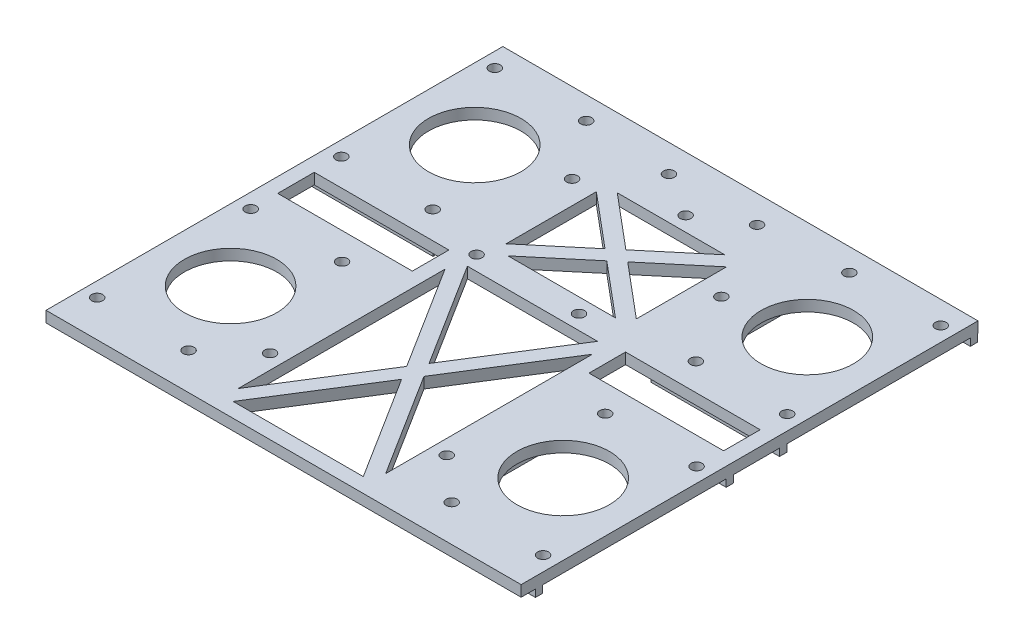
SolidWorks part; units mm, degrees
ref_plane "Front Plane" through (0, 0, 0) normal (0, 0, 1) x (1, 0, 0)
ref_plane "Top Plane" through (0, 0, 0) normal (0, 1, 0) x (1, 0, 0)
ref_plane "Right Plane" through (0, 0, 0) normal (1, 0, 0) x (0, 0, -1)
sketch "Sketch1" plane through (0, 0, 0) normal (0, 1, 0) x (1, 0, 0)
  line L1 (-65, 62.5) -> (65, 62.5)
  line L2 (-65, 62.5) -> (-65, -62.5)
  line L3 (-65, -62.5) -> (65, -62.5)
  line L4 (65, 62.5) -> (65, -62.5)
  line L5 (-65, 62.5) -> (65, -62.5) construction
  line L6 (-65, -62.5) -> (65, 62.5) construction
  point P0 (0, 0)
  dimension "D1" = 130
  dimension "D2" = 125
extrude "Boss-Extrude1" add sketch "Sketch1" along normal blind 5
sketch "Sketch2" plane through (0, 5, 0) normal (0, 1, 0) x (1, 0, 0)
  line L1 (-65, -62.5) -> (65, -62.5) construction
  line L2 (-65, 62.5) -> (-65, -62.5) construction
  circle A0 centre (-61, -52.5) radius 1.5
  circle A1 centre (-36, -52.5) radius 1.5
  circle A2 centre (-36, -10.5) radius 1.5
  circle A3 centre (-61, -10.5) radius 1.5
  circle A4 centre (-45.5, -31.5) radius 12.65
  dimension "D2" = 25.3
  dimension "D7" = 3
  dimension "D8" = 3
  dimension "D9" = 3
  dimension "D10" = 3
  dimension "D1" = 19.5
  dimension "D3" = 31
  dimension "D4" = 4
  dimension "D5" = 10
  dimension "D6" = 10
  dimension "D11" = 4
  dimension "D12" = 42
  dimension "D13" = 42
  dimension "D14" = 25
  dimension "D15" = 25
extrude "Cut-Extrude1" cut sketch "Sketch2" against normal blind 10
ref_plane "Plane1" through (0, 0, 0) normal (-1, 0, 0) x (0, 0, 1)
ref_plane "Plane2" through (0, 0, 0) normal (0, 0, 1) x (1, 0, 0)
mirror "Mirror3" about plane through (0, 0, 0) normal (-1, 0, 0) of "Cut-Extrude1"
sketch "Sketch4" plane through (0, 5, 0) normal (0, 1, 0) x (1, 0, 0)
  line L0 (0, 62.5) -> (0, 47.5) construction
  line L1 (65, 62.5) -> (-65, 62.5) construction
  line L2 (-12.0498, 55) -> (12.0498, 55) construction
  circle A0 centre (0, 47.5) radius 1.5
  circle A1 centre (12.0498, 55) radius 1.5
  circle A2 centre (-12.0498, 55) radius 1.5
  point P9 (0, 55)
  dimension "D2" = 3
  dimension "D3" = 3
  dimension "D4" = 3
  dimension "D1" = 15
  dimension "D5" = 24.0996
extrude "Cut-Extrude3" cut sketch "Sketch4" against normal blind 10
sketch "Sketch5" plane through (0, 0, 0) normal (0, -1, 0) x (1, 0, 0)
  line L0 (-58.15, 31.5) -> (-65, 31.5) construction
  line L1 (-65, -62.5) -> (-65, 62.5) construction
  line L2 (-65, 56.6) -> (-65, 6.4)
  line L3 (-65, 56.6) -> (-31.8, 56.6)
  line L4 (-31.8, 56.6) -> (-31.8, 6.4)
  line L5 (-31.8, 6.4) -> (-65, 6.4)
  line L6 (-65, 58.6) -> (-29.8, 58.6)
  line L7 (-29.8, 58.6) -> (-29.8, 4.4)
  line L8 (-29.8, 4.4) -> (-65, 4.4)
  line L9 (-65, 4.4) -> (-65, 6.4)
  line L10 (-65, 58.6) -> (-65, 56.6)
  circle A0 centre (-45.5, 31.5) radius 12.65 construction
  point P10 (-65, 31.5)
  line M39 (-65, 62.5) -> (-65, -62.5)
  dimension "D1" = 50.2
  dimension "D2" = 33.2
  dimension "D3" = 2
  dimension "D4" = 2
  dimension "D5" = 2
extrude "Boss-Extrude2" add sketch "Sketch5" along normal blind 2 contours L8 L7 L6 L3 L4 L5 M39
mirror "Mirror5" about plane through (0, 0, 0) normal (-1, 0, 0) of "Boss-Extrude2"
ref_plane "Plane3" through (0, 0, 0) normal (0, 0, 1) x (1, 0, 0)
ref_plane "Plane4" through (0, 0, -1.9) normal (0, 0, 1) x (1, 0, 0)
mirror "Mirror7" about plane through (0, 0, -1.9) normal (0, 0, 1) of "Mirror5", "Boss-Extrude2", "Mirror3", "Cut-Extrude1"
ref_plane "Plane5" through (0, 0, 0) normal (0, -1, 0) x (-1, 0, 0)
sketch "Sketch10" plane through (0, 0, 0) normal (0, -1, 0) x (-1, 0, 0)
  circle A0 centre (-24.17, -42.03) radius 1.5
  circle A1 centre (24.17, -42.03) radius 1.5
  circle A2 centre (-8.73, 9.6) radius 1.5
  circle A3 centre (19.29, 9.6) radius 1.5
  circle A4 centre (-24.17, 33.11) radius 1.5
  circle A5 centre (24.17, 40.6) radius 1.5
  dimension "D1" = 3
  dimension "D6" = 3
  dimension "D7" = 3
  dimension "D10" = 3
  dimension "D11" = 3
  dimension "D12" = 3
extrude "Cut-Extrude8" cut sketch "Sketch10" against normal through all
sketch "Sketch11" plane through (0, 0, 0) normal (0, -1, 0) x (1, 0, 0)
  circle A0 centre (-12.0498, -55) radius 2.65
  circle A1 centre (0, -47.5) radius 2.65
  circle A2 centre (12.0498, -55) radius 2.65
  circle A3 centre (-24.17, -40.6) radius 2.65
  circle A4 centre (24.17, -33.11) radius 2.65
  circle A5 centre (8.73, -9.6) radius 2.65
  circle A6 centre (-19.29, -9.6) radius 2.65
  circle A7 centre (-24.17, 42.03) radius 2.65
  circle A8 centre (24.17, 42.03) radius 2.65
  circle A9 centre (-61, -14.3) radius 2.65
  circle A10 centre (-36, -14.3) radius 2.65
  circle A11 centre (-61, -56.3) radius 2.65
  circle A12 centre (-36, -56.3) radius 2.65
  circle A13 centre (36, -56.3) radius 2.65
  circle A14 centre (61, -56.3) radius 2.65
  circle A15 centre (36, -14.3) radius 2.65
  circle A16 centre (61, -14.3) radius 2.65
  circle A17 centre (36, 10.5) radius 2.65
  circle A18 centre (61, 10.5) radius 2.65
  circle A19 centre (61, 52.5) radius 2.65
  circle A20 centre (36, 52.5) radius 2.65
  circle A21 centre (-36, 52.5) radius 2.65
  circle A22 centre (-36, 10.5) radius 2.65
  circle A23 centre (-61, 10.5) radius 2.65
  circle A24 centre (-61, 52.5) radius 2.65
  dimension "D1" = 5.3
  dimension "D2" = 5.3
  dimension "D3" = 5.3
  dimension "D4" = 5.3
  dimension "D5" = 5.3
  dimension "D6" = 5.3
  dimension "D7" = 5.3
  dimension "D8" = 5.3
  dimension "D9" = 5.3
  dimension "D10" = 5.3
  dimension "D11" = 5.3
  dimension "D12" = 5.3
  dimension "D13" = 5.3
  dimension "D14" = 5.3
  dimension "D15" = 5.3
  dimension "D16" = 5.3
  dimension "D17" = 5.3
  dimension "D18" = 5.3
  dimension "D19" = 5.3
  dimension "D20" = 5.3
  dimension "D21" = 5.3
  dimension "D22" = 5.3
  dimension "D23" = 5.3
  dimension "D24" = 5.3
  dimension "D25" = 5.3
extrude "Cut-Extrude9" cut sketch "Sketch11" against normal blind 0.5
sketch "Sketch12" plane through (0, 5, 0) normal (0, 1, 0) x (1, 0, 0)
  line L0 (-65, -62.5) -> (65, -62.5) construction
  line L1 (-20.17, 5.6) -> (20.17, 5.6)
  line L2 (-20.17, 5.6) -> (-20.17, -58.5)
  line L3 (-20.17, -58.5) -> (20.17, -58.5)
  line L4 (20.17, 5.6) -> (20.17, -58.5)
  line L5 (-20.17, 5.6) -> (20.17, -58.5) construction
  line L6 (-20.17, -58.5) -> (20.17, 5.6) construction
  line L7 (-17.8069, 5.6) -> (0, -22.6951)
  line L8 (20.17, -54.7451) -> (2.3631, -26.45)
  line L9 (2.3631, -26.45) -> (20.17, 1.8451)
  line L10 (0, -22.6951) -> (17.8069, 5.6)
  line L11 (-20.17, 1.8451) -> (-2.3631, -26.45)
  line L12 (-2.3631, -26.45) -> (-20.17, -54.7451)
  line L13 (-17.8069, -58.5) -> (0, -30.2049)
  line L14 (0, -30.2049) -> (17.8069, -58.5)
  circle A0 centre (-19.29, 9.6) radius 1.5 construction
  circle A1 centre (-24.17, -42.03) radius 1.5 construction
  circle A2 centre (24.17, -42.03) radius 1.5 construction
  dimension "D2" = 4
  dimension "D3" = 4
  dimension "D1" = 4
  dimension "D4" = 4
  dimension "D5" = 2
  dimension "D6" = 2
  dimension "D7" = 2
  dimension "D8" = 2
extrude "Cut-Extrude10" cut sketch "Sketch12" against normal through all contours L12 L11 L2 | L7 L10 L1 | L9 L8 L4 | L14 L13 L3
sketch "Sketch13" plane through (0, 5, 0) normal (0, 1, 0) x (1, 0, 0)
  line L0 (-61, 14.3) -> (-61, -10.5) construction
  line L1 (-61, 1.9) -> (-61, -3.1)
  line L2 (-61, -3.1) -> (-24.17, -3.1)
  line L3 (-24.17, -3.1) -> (-24.17, 6.9)
  line L4 (-24.17, 6.9) -> (-61, 6.9)
  line L5 (-61, 6.9) -> (-61, 1.9)
  line L6 (-20.17, 1.8451) -> (-20.17, -54.7451) construction
  dimension "D1" = 10
  dimension "D2" = 5
  dimension "D3" = 4
extrude "Cut-Extrude11" cut sketch "Sketch13" against normal through all
mirror "Mirror9" about plane through (0, 0, 0) normal (-1, 0, 0) of "Cut-Extrude11"
sketch "Sketch14" plane through (0, 5, 0) normal (0, 1, 0) x (1, 0, 0)
  line L0 (-17.8069, 43.5) -> (17.8069, 13.6) construction
  line L1 (-17.8069, 43.5) -> (17.8069, 43.5)
  line L2 (-17.8069, 43.5) -> (-17.8069, 13.6)
  line L3 (-17.8069, 13.6) -> (17.8069, 13.6)
  line L4 (17.8069, 43.5) -> (17.8069, 13.6)
  line L5 (-17.8069, 13.6) -> (17.8069, 43.5) construction
  line L6 (-17.8069, 40.8886) -> (-3.1104, 28.55)
  line L7 (-3.1104, 28.55) -> (-17.8069, 16.2114)
  line L8 (-14.6965, 13.6) -> (0, 25.9386)
  line L9 (0, 25.9386) -> (14.6965, 13.6)
  line L10 (17.8069, 16.2114) -> (3.1104, 28.55)
  line L11 (3.1104, 28.55) -> (17.8069, 40.8886)
  line L12 (14.6965, 43.5) -> (0, 31.1614)
  line L13 (0, 31.1614) -> (-14.6965, 43.5)
  circle A0 centre (0, 47.5) radius 1.5 construction
  circle A1 centre (8.73, 9.6) radius 1.5 construction
  dimension "D1" = 4
  dimension "D2" = 4
  dimension "D3" = 2
  dimension "D4" = 2
  dimension "D5" = 2
  dimension "D6" = 2
  dimension "D7" = 2
  dimension "D8" = 2
  dimension "D9" = 2
  dimension "D10" = 2
extrude "Cut-Extrude12" cut sketch "Sketch14" against normal through all contours L7 L6 L2 | L13 L12 L1 | L11 L10 L4 | L9 L8 L3
sketch "Sketch15" plane through (0, 5, 0) normal (0, 1, 0) x (1, 0, 0)
  line L1 (-63.5, 58.8) -> (-58.5, 58.8)
  line L2 (-63.5, 58.8) -> (-63.5, 53.8)
  line L3 (-63.5, 53.8) -> (-58.5, 53.8)
  line L4 (65, -62.5) -> (65, 62.5)
  line L5 (65, 62.5) -> (-65, 62.5)
  line L6 (-65, 62.5) -> (-65, -62.5)
  line L7 (-65, -62.5) -> (65, -62.5)
  line L8 (65, -62.5) -> (65, 62.5)
  line L9 (65, 62.5) -> (-65, 62.5)
  line L10 (-65, 62.5) -> (-65, -62.5)
  line L11 (-65, -62.5) -> (65, -62.5)
  line L12 (-58.5, 58.8) -> (-58.5, 53.8)
  line L13 (-63.5, 58.8) -> (-58.5, 53.8) construction
  line L14 (-63.5, 53.8) -> (-58.5, 58.8) construction
  line L15 (-38.5, 58.8) -> (-33.5, 58.8)
  line L16 (-38.5, 58.8) -> (-38.5, 53.8)
  line L17 (-38.5, 53.8) -> (-33.5, 53.8)
  line L18 (-33.5, 58.8) -> (-33.5, 53.8)
  line L19 (-38.5, 58.8) -> (-33.5, 53.8) construction
  line L20 (-38.5, 53.8) -> (-33.5, 58.8) construction
  line L21 (-14.5498, 57.5) -> (-9.5498, 57.5)
  line L22 (-14.5498, 57.5) -> (-14.5498, 52.5)
  line L23 (-14.5498, 52.5) -> (-9.5498, 52.5)
  line L24 (-9.5498, 57.5) -> (-9.5498, 52.5)
  line L25 (-14.5498, 57.5) -> (-9.5498, 52.5) construction
  line L26 (-14.5498, 52.5) -> (-9.5498, 57.5) construction
  line L27 (-2.5, 50) -> (2.5, 50)
  line L28 (-2.5, 50) -> (-2.5, 45)
  line L29 (-2.5, 45) -> (2.5, 45)
  line L30 (2.5, 50) -> (2.5, 45)
  line L31 (-2.5, 50) -> (2.5, 45) construction
  line L32 (-2.5, 45) -> (2.5, 50) construction
  line L33 (9.5498, 57.5) -> (14.5498, 57.5)
  line L34 (9.5498, 57.5) -> (9.5498, 52.5)
  line L35 (9.5498, 52.5) -> (14.5498, 52.5)
  line L36 (14.5498, 57.5) -> (14.5498, 52.5)
  line L37 (9.5498, 57.5) -> (14.5498, 52.5) construction
  line L38 (9.5498, 52.5) -> (14.5498, 57.5) construction
  line L39 (33.5, 58.8) -> (38.5, 58.8)
  line L40 (33.5, 58.8) -> (33.5, 53.8)
  line L41 (33.5, 53.8) -> (38.5, 53.8)
  line L42 (38.5, 58.8) -> (38.5, 53.8)
  line L43 (33.5, 58.8) -> (38.5, 53.8) construction
  line L44 (33.5, 53.8) -> (38.5, 58.8) construction
  line L45 (63.5, 58.8) -> (58.5, 58.8)
  line L46 (63.5, 58.8) -> (63.5, 53.8)
  line L47 (63.5, 53.8) -> (58.5, 53.8)
  line L48 (58.5, 58.8) -> (58.5, 53.8)
  line L49 (63.5, 58.8) -> (58.5, 53.8) construction
  line L50 (63.5, 53.8) -> (58.5, 58.8) construction
  line L51 (33.5, 16.8) -> (38.5, 16.8)
  line L52 (33.5, 16.8) -> (33.5, 11.8)
  line L53 (33.5, 11.8) -> (38.5, 11.8)
  line L54 (38.5, 16.8) -> (38.5, 11.8)
  line L55 (33.5, 16.8) -> (38.5, 11.8) construction
  line L56 (33.5, 11.8) -> (38.5, 16.8) construction
  line L57 (63.5, 16.8) -> (58.5, 16.8)
  line L58 (63.5, 16.8) -> (63.5, 11.8)
  line L59 (63.5, 11.8) -> (58.5, 11.8)
  line L60 (58.5, 16.8) -> (58.5, 11.8)
  line L61 (63.5, 16.8) -> (58.5, 11.8) construction
  line L62 (63.5, 11.8) -> (58.5, 16.8) construction
  line L63 (21.67, 35.61) -> (26.67, 35.61)
  line L64 (21.67, 35.61) -> (21.67, 30.61)
  line L65 (21.67, 30.61) -> (26.67, 30.61)
  line L66 (26.67, 35.61) -> (26.67, 30.61)
  line L67 (21.67, 35.61) -> (26.67, 30.61) construction
  line L68 (21.67, 30.61) -> (26.67, 35.61) construction
  line L69 (33.5, -8) -> (38.5, -8)
  line L70 (33.5, -8) -> (33.5, -13)
  line L71 (33.5, -13) -> (38.5, -13)
  line L72 (38.5, -8) -> (38.5, -13)
  line L73 (33.5, -8) -> (38.5, -13) construction
  line L74 (33.5, -13) -> (38.5, -8) construction
  line L75 (63.5, -8) -> (58.5, -8)
  line L76 (63.5, -8) -> (63.5, -13)
  line L77 (63.5, -13) -> (58.5, -13)
  line L78 (58.5, -8) -> (58.5, -13)
  line L79 (63.5, -8) -> (58.5, -13) construction
  line L80 (63.5, -13) -> (58.5, -8) construction
  line L81 (21.67, -39.53) -> (26.67, -39.53)
  line L82 (21.67, -39.53) -> (21.67, -44.53)
  line L83 (21.67, -44.53) -> (26.67, -44.53)
  line L84 (26.67, -39.53) -> (26.67, -44.53)
  line L85 (21.67, -39.53) -> (26.67, -44.53) construction
  line L86 (21.67, -44.53) -> (26.67, -39.53) construction
  line L87 (38.5, -50) -> (33.5, -50)
  line L88 (38.5, -50) -> (38.5, -55)
  line L89 (38.5, -55) -> (33.5, -55)
  line L90 (33.5, -50) -> (33.5, -55)
  line L91 (38.5, -50) -> (33.5, -55) construction
  line L92 (38.5, -55) -> (33.5, -50) construction
  line L93 (63.5, -50) -> (58.5, -50)
  line L94 (63.5, -50) -> (63.5, -55)
  line L95 (63.5, -55) -> (58.5, -55)
  line L96 (58.5, -50) -> (58.5, -55)
  line L97 (63.5, -50) -> (58.5, -55) construction
  line L98 (63.5, -55) -> (58.5, -50) construction
  line L99 (-26.67, -39.53) -> (-21.67, -39.53)
  line L100 (-26.67, -39.53) -> (-26.67, -44.53)
  line L101 (-26.67, -44.53) -> (-21.67, -44.53)
  line L102 (-21.67, -39.53) -> (-21.67, -44.53)
  line L103 (-26.67, -39.53) -> (-21.67, -44.53) construction
  line L104 (-26.67, -44.53) -> (-21.67, -39.53) construction
  line L105 (-38.5, -50) -> (-33.5, -50)
  line L106 (-38.5, -50) -> (-38.5, -55)
  line L107 (-38.5, -55) -> (-33.5, -55)
  line L108 (-33.5, -50) -> (-33.5, -55)
  line L109 (-38.5, -50) -> (-33.5, -55) construction
  line L110 (-38.5, -55) -> (-33.5, -50) construction
  line L111 (-38.5, -8) -> (-33.5, -8)
  line L112 (-38.5, -8) -> (-38.5, -13)
  line L113 (-38.5, -13) -> (-33.5, -13)
  line L114 (-33.5, -8) -> (-33.5, -13)
  line L115 (-38.5, -8) -> (-33.5, -13) construction
  line L116 (-38.5, -13) -> (-33.5, -8) construction
  line L117 (6.23, 12.1) -> (11.23, 12.1)
  line L118 (6.23, 12.1) -> (6.23, 7.1)
  line L119 (6.23, 7.1) -> (11.23, 7.1)
  line L120 (11.23, 12.1) -> (11.23, 7.1)
  line L121 (6.23, 12.1) -> (11.23, 7.1) construction
  line L122 (6.23, 7.1) -> (11.23, 12.1) construction
  line L123 (-21.79, 12.1) -> (-16.79, 12.1)
  line L124 (-21.79, 12.1) -> (-21.79, 7.1)
  line L125 (-21.79, 7.1) -> (-16.79, 7.1)
  line L126 (-16.79, 12.1) -> (-16.79, 7.1)
  line L127 (-21.79, 12.1) -> (-16.79, 7.1) construction
  line L128 (-21.79, 7.1) -> (-16.79, 12.1) construction
  line L129 (-26.67, 43.1) -> (-21.67, 43.1)
  line L130 (-26.67, 43.1) -> (-26.67, 38.1)
  line L131 (-26.67, 38.1) -> (-21.67, 38.1)
  line L132 (-21.67, 43.1) -> (-21.67, 38.1)
  line L133 (-26.67, 43.1) -> (-21.67, 38.1) construction
  line L134 (-26.67, 38.1) -> (-21.67, 43.1) construction
  line L135 (-63.5, 16.8) -> (-58.5, 16.8)
  line L136 (-63.5, 16.8) -> (-63.5, 11.8)
  line L137 (-63.5, 11.8) -> (-58.5, 11.8)
  line L138 (-58.5, 16.8) -> (-58.5, 11.8)
  line L139 (-63.5, 16.8) -> (-58.5, 11.8) construction
  line L140 (-63.5, 11.8) -> (-58.5, 16.8) construction
  line L141 (-38.5, 16.8) -> (-33.5, 16.8)
  line L142 (-38.5, 16.8) -> (-38.5, 11.8)
  line L143 (-38.5, 11.8) -> (-33.5, 11.8)
  line L144 (-33.5, 16.8) -> (-33.5, 11.8)
  line L145 (-38.5, 16.8) -> (-33.5, 11.8) construction
  line L146 (-38.5, 11.8) -> (-33.5, 16.8) construction
  line L147 (-63.5, -8) -> (-58.5, -8)
  line L148 (-63.5, -8) -> (-63.5, -13)
  line L149 (-63.5, -13) -> (-58.5, -13)
  line L150 (-58.5, -8) -> (-58.5, -13)
  line L151 (-63.5, -8) -> (-58.5, -13) construction
  line L152 (-63.5, -13) -> (-58.5, -8) construction
  line L153 (-63.5, -50) -> (-58.5, -50)
  line L154 (-63.5, -50) -> (-63.5, -55)
  line L155 (-63.5, -55) -> (-58.5, -55)
  line L156 (-58.5, -50) -> (-58.5, -55)
  line L157 (-63.5, -50) -> (-58.5, -55) construction
  line L158 (-63.5, -55) -> (-58.5, -50) construction
  circle A0 centre (-61, 56.3) radius 1.5 construction
  circle A1 centre (-36, 56.3) radius 1.5 construction
  circle A2 centre (-12.0498, 55) radius 1.5 construction
  circle A3 centre (0, 47.5) radius 1.5 construction
  circle A4 centre (12.0498, 55) radius 1.5 construction
  circle A5 centre (36, 56.3) radius 1.5 construction
  circle A6 centre (61, 56.3) radius 1.5 construction
  circle A7 centre (24.17, 33.11) radius 1.5 construction
  circle A8 centre (36, 14.3) radius 1.5 construction
  circle A9 centre (61, 14.3) radius 1.5 construction
  circle A10 centre (-24.17, 40.6) radius 1.5 construction
  circle A11 centre (-61, 14.3) radius 1.5 construction
  circle A12 centre (-36, 14.3) radius 1.5 construction
  circle A13 centre (-19.29, 9.6) radius 1.5 construction
  circle A14 centre (8.73, 9.6) radius 1.5 construction
  circle A15 centre (-61, -10.5) radius 1.5 construction
  circle A16 centre (-36, -10.5) radius 1.5 construction
  circle A17 centre (36, -10.5) radius 1.5 construction
  circle A18 centre (61, -10.5) radius 1.5 construction
  circle A19 centre (61, -52.5) radius 1.5 construction
  circle A20 centre (36, -52.5) radius 1.5 construction
  circle A21 centre (24.17, -42.03) radius 1.5 construction
  circle A22 centre (-24.17, -42.03) radius 1.5 construction
  circle A23 centre (-36, -52.5) radius 1.5 construction
  circle A24 centre (-61, -52.5) radius 1.5 construction
  point P2 (-61, 56.3)
  point P12 (-36, 56.3)
  point P20 (-12.0498, 55)
  point P26 (0, 47.5)
  point P32 (12.0498, 55)
  point P38 (36, 56.3)
  point P44 (61, 56.3)
  point P50 (36, 14.3)
  point P56 (61, 14.3)
  point P62 (24.17, 33.11)
  point P84 (36, -10.5)
  point P90 (61, -10.5)
  point P96 (24.17, -42.03)
  point P102 (36, -52.5)
  point P108 (61, -52.5)
  point P114 (-24.17, -42.03)
  point P120 (-36, -52.5)
  point P126 (-36, -10.5)
  point P132 (8.73, 9.6)
  point P138 (-19.29, 9.6)
  point P144 (-24.17, 40.6)
  point P150 (-61, 14.3)
  point P156 (-36, 14.3)
  point P162 (-61, -10.5)
  point P168 (-61, -52.5)
  dimension "D2" = 2.5
  dimension "D3" = 2.5
  dimension "D4" = 2.5
  dimension "D5" = 2.5
  dimension "D6" = 2.5
  dimension "D7" = 2.5
  dimension "D8" = 2.5
  dimension "D9" = 2.5
  dimension "D10" = 2.5
  dimension "D11" = 2.5
  dimension "D12" = 2.5
  dimension "D13" = 2.5
  dimension "D15" = 2.5
  dimension "D16" = 2.5
  dimension "D17" = 2.5
  dimension "D18" = 2.5
  dimension "D19" = 2.5
  dimension "D20" = 2.5
  dimension "D21" = 2.5
  dimension "D22" = 2.5
  dimension "D23" = 2.5
  dimension "D24" = 2.5
  dimension "D25" = 2.5
  dimension "D26" = 2.5
  dimension "D27" = 2.5
  dimension "D28" = 2.5
  dimension "D29" = 2.5
  dimension "D30" = 2.5
  dimension "D31" = 2.5
  dimension "D32" = 2.5
  dimension "D33" = 2.5
  dimension "D34" = 2.5
  dimension "D35" = 2.5
  dimension "D36" = 2.5
  dimension "D37" = 2.5
  dimension "D38" = 2.5
  dimension "D39" = 2.5
  dimension "D40" = 2.5
  dimension "D41" = 2.5
  dimension "D42" = 2.5
  dimension "D43" = 2.5
  dimension "D44" = 2.5
  dimension "D45" = 2.5
  dimension "D46" = 2.5
  dimension "D47" = 2.5
  dimension "D48" = 2.5
  dimension "D49" = 2.5
  dimension "D14" = 2.5
  dimension "D1" = 0
extrude "Cut-Extrude14" cut sketch "Sketch15" against normal blind 2
ref_plane "Plane6" through (0, 13, 0) normal (0, 1, 0) x (1, 0, 0)
sketch "Sketch17" plane through (0, 13, 0) normal (0, 1, 0) x (1, 0, 0)
  line L1 (-68.0587, 64.2777) -> (69.5711, 64.2777)
  line L2 (-68.0587, 64.2777) -> (-68.0587, -66.7984)
  line L3 (-68.0587, -66.7984) -> (69.5711, -66.7984)
  line L4 (69.5711, 64.2777) -> (69.5711, -66.7984)
extrude "Cut-Extrude15" cut sketch "Sketch17" against normal blind 2 from surface at -8 starting at face at (-61, 5, -15.8)
